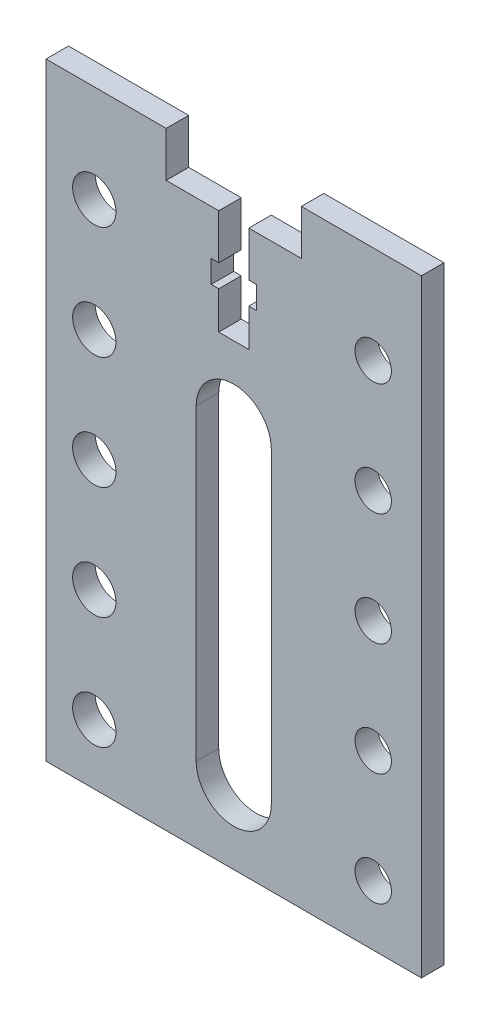
SolidWorks part; units mm, degrees
ref_plane "Plan de face" through (0, 0, 0) normal (0, 0, 1) x (1, 0, 0)
ref_plane "Plan de dessus" through (0, 0, 0) normal (0, 1, 0) x (1, 0, 0)
ref_plane "Plan de droite" through (0, 0, 0) normal (1, 0, 0) x (0, 0, -1)
sketch "Esquisse1" plane through (0, 0, 0) normal (0, 0, 1) x (1, 0, 0)
  line L1 (-41.1663, 53.6766) -> (8.8337, 53.6766)
  line L2 (-41.1663, 53.6766) -> (-41.1663, -27.3234)
  line L3 (-41.1663, -27.3234) -> (8.8337, -27.3234)
  line L4 (8.8337, 53.6766) -> (8.8337, -27.3234)
  dimension "D1" = 81
  dimension "D2" = 50
extrude "Boss.-Extru.1" add sketch "Esquisse1" along normal blind 3
sketch "Esquisse2" plane through (0, 0, 3) normal (0, 0, 1) x (1, 0, 0)
  line L0 (-16.1663, 53.6766) -> (-16.1663, 31.1366) construction
  line L1 (8.8337, 53.6766) -> (-41.1663, 53.6766) construction
  line L2 (-41.1663, 47.6766) -> (8.8337, 47.6766) construction
  line L3 (-25.1663, 53.6766) -> (-7.1663, 53.6766)
  line L4 (-25.1663, 53.6766) -> (-25.1663, 47.6766)
  line L5 (-25.1663, 47.6766) -> (-7.1663, 47.6766)
  line L6 (-7.1663, 53.6766) -> (-7.1663, 47.6766)
  line L7 (-41.1663, 53.6766) -> (-41.1663, -27.3234) construction
  line L8 (8.8337, -27.3234) -> (8.8337, 53.6766) construction
  dimension "D1" = 6
  dimension "D2" = 18
extrude "Enlèv. mat.-Extru.1" cut sketch "Esquisse2" against normal blind 3
sketch "Esquisse3" plane through (0, 0, 3) normal (0, 0, 1) x (1, 0, 0)
  line L0 (-16.1663, 47.6766) -> (-16.1663, -27.3234) construction
  line L1 (-25.1663, 47.6766) -> (-7.1663, 47.6766) construction
  line L2 (-41.1663, -27.3234) -> (8.8337, -27.3234) construction
  line L3 (-18.1663, 41.6766) -> (-19.1663, 41.6766)
  line L4 (-18.1663, 47.6766) -> (-14.1663, 47.6766)
  line L5 (-18.1663, 47.6766) -> (-18.1663, 41.6766)
  line L6 (-18.1663, 38.6766) -> (-19.1663, 38.6766)
  line L7 (-14.1663, 47.6766) -> (-14.1663, 41.6766)
  line L8 (-13.1663, 41.6766) -> (-14.1663, 41.6766)
  line L9 (-13.1663, 41.6766) -> (-13.1663, 38.6766)
  line L10 (-13.1663, 38.6766) -> (-14.1663, 38.6766)
  line L11 (-19.1663, 41.6766) -> (-19.1663, 38.6766)
  line L12 (-16.1663, 23.6766) -> (-16.1663, -17.3234) construction
  line L13 (-18.1663, 38.6766) -> (-18.1663, 33.6766)
  line L14 (-18.1663, 33.6766) -> (-14.1663, 33.6766)
  line L15 (-14.1663, 38.6766) -> (-14.1663, 33.6766)
  line L16 (-11.1663, 23.6766) -> (-11.1663, -17.3234)
  line L17 (-21.1663, 23.6766) -> (-21.1663, -17.3234)
  arc A0 (-11.1663, 23.6766) -> (-21.1663, 23.6766) centre (-16.1663, 23.6766) ccw
  arc A1 (-21.1663, -17.3234) -> (-11.1663, -17.3234) centre (-16.1663, -17.3234) ccw
  point P20 (-16.1663, 3.1766)
  dimension "D1" = 4
  dimension "D2" = 1
  dimension "D3" = 3
  dimension "D4" = 6
  dimension "D5" = 5
  dimension "D6" = 10
  dimension "D7" = 10
  dimension "D8" = 10
extrude "Enlèv. mat.-Extru.2" cut sketch "Esquisse3" against normal blind 3
sketch "Esquisse5" plane through (0, 0, 3) normal (0, 0, 1) x (1, 0, 0)
  line L0 (-16.1663, -27.3234) -> (-16.1663, 33.6766) construction
  line L1 (-41.1663, -27.3234) -> (8.8337, -27.3234) construction
  line L2 (-18.1663, 33.6766) -> (-14.1663, 33.6766) construction
  circle A0 centre (-34.7413, -19.3234) radius 2.8856
  circle A1 centre (2.4087, -19.3234) radius 2.4232
  circle A2 centre (-34.7413, -4.3234) radius 2.8856
  circle A3 centre (2.4087, -4.3234) radius 2.4232
  circle A4 centre (-34.7413, 10.6766) radius 2.8856
  circle A5 centre (2.4087, 10.6766) radius 2.4232
  circle A6 centre (-34.7413, 25.6766) radius 2.8856
  circle A7 centre (2.4087, 25.6766) radius 2.4232
  circle A8 centre (-34.7413, 40.6766) radius 2.8856
  circle A9 centre (2.4087, 40.6766) radius 2.4232
  dimension "D1" = 37.15
  dimension "D2" = 8
  dimension "D3" = 5
extrude "Enlèv. mat.-Extru.3" cut sketch "Esquisse5" against normal blind 3
